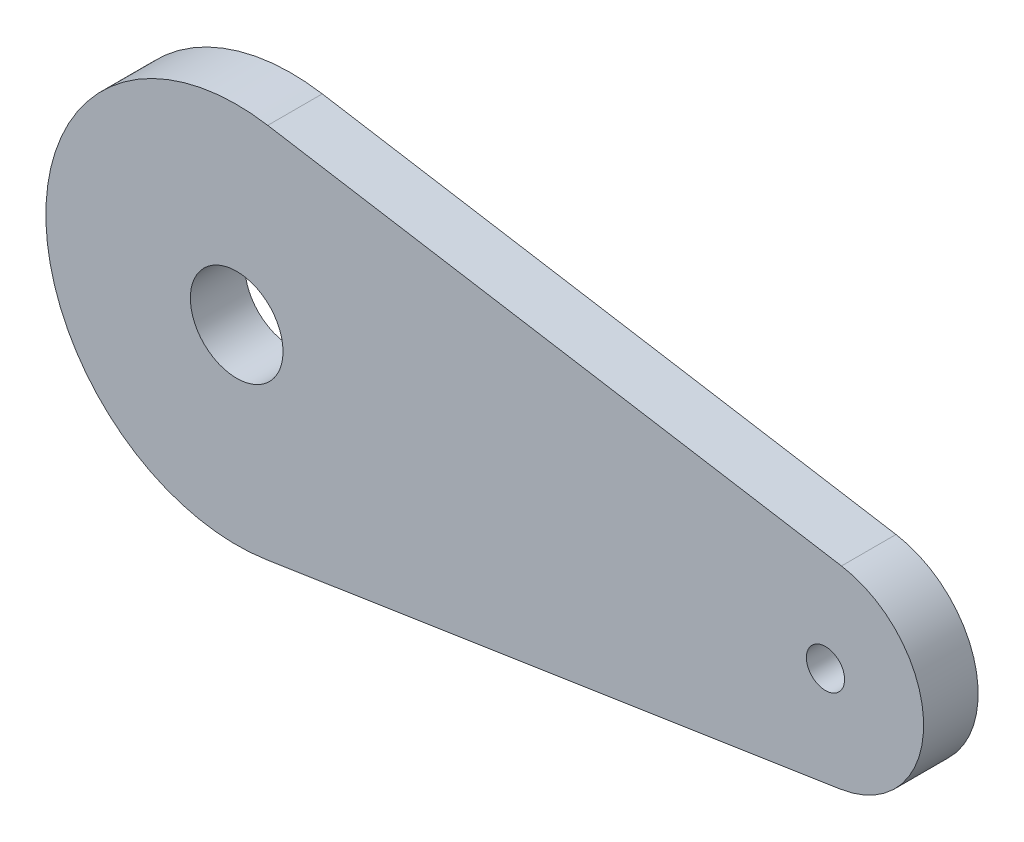
SolidWorks part; units mm, degrees
ref_plane "Front Plane" through (0, 0, 0) normal (0, 0, 1) x (1, 0, 0)
ref_plane "Top Plane" through (0, 0, 0) normal (0, 1, 0) x (1, 0, 0)
ref_plane "Right Plane" through (0, 0, 0) normal (1, 0, 0) x (0, 0, -1)
sketch "Sketch1" plane through (0, 0, 0) normal (0, 0, 1) x (1, 0, 0)
  line L0 (-20.22, 57.58) -> (33.7792, 57.2801) construction
  line L1 (-20.22, 57.58) -> (33.7792, 57.2801) construction
  line L2 (-17.3694, 74.8463) -> (35.2452, 66.1599)
  line L3 (-17.5614, 40.2831) -> (35.1464, 48.3845)
  circle A0 centre (-20.22, 57.58) radius 17.5 construction
  circle A1 centre (-20.22, 57.58) radius 17.5 construction
  circle A2 centre (33.7792, 57.2801) radius 9 construction
  arc A3 (-17.3694, 74.8463) -> (-17.5614, 40.2831) centre (-20.22, 57.58) ccw
  arc A4 (35.2452, 66.1599) -> (35.1464, 48.3845) centre (33.7792, 57.2801) cw
  circle A5 centre (-20.22, 57.58) radius 4.25
  circle A6 centre (33.7792, 57.2801) radius 1.75
  dimension "D1" = 18
  dimension "D2" = 3.5
  dimension "D3" = 8.5
extrude "Boss-Extrude1" add sketch "Sketch1" against normal blind 5
